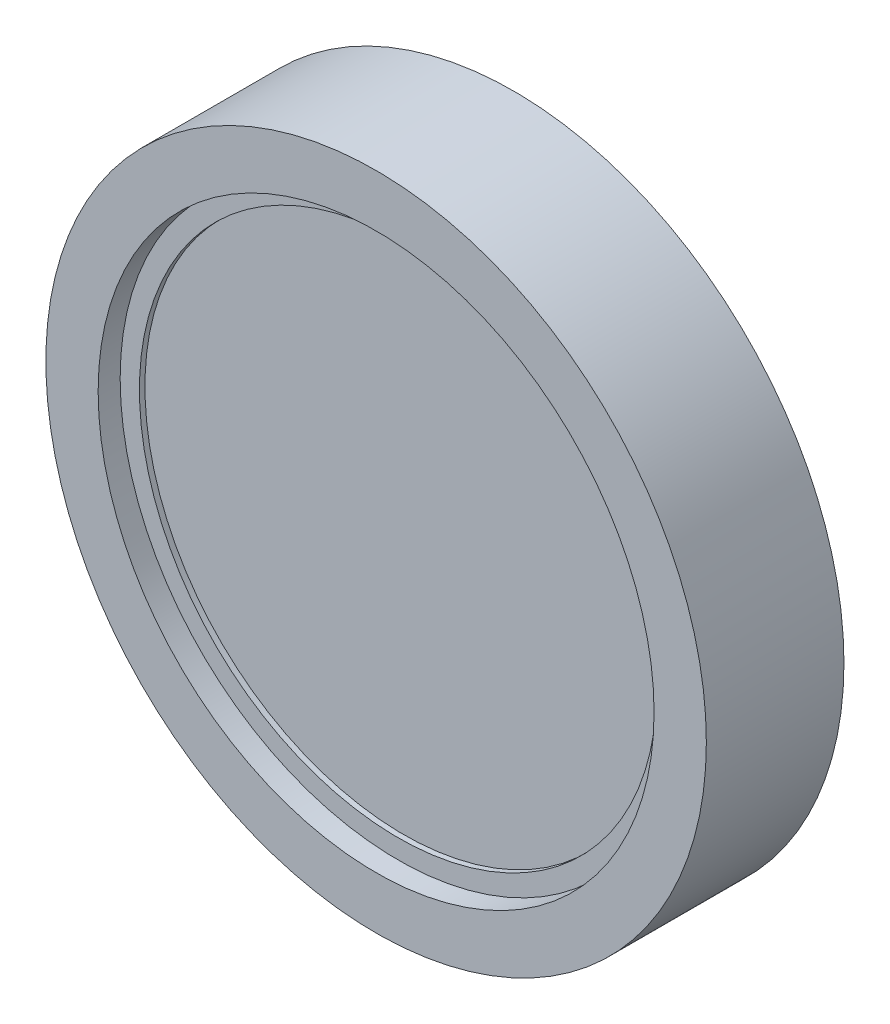
SolidWorks part; units mm, degrees
material "6061 Alloy"
ref_plane "Front Plane" through (0, 0, 0) normal (0, 0, 1) x (1, 0, 0)
ref_plane "Top Plane" through (0, 0, 0) normal (0, 1, 0) x (1, 0, 0)
ref_plane "Right Plane" through (0, 0, 0) normal (1, 0, 0) x (0, 0, -1)
sketch "Backer Main" plane through (0, 0, 0) normal (0, 0, 1) x (1, 0, 0)
  circle A0 centre (0, 0) radius 15.24
  dimension "D1" = 30.48
extrude "Boss-Extrude1" add sketch "Backer Main" against normal blind 6.35
sketch "Substrate Back Clearance" plane through (0, 0, 0) normal (0, 0, 1) x (1, 0, 0)
  circle A0 centre (0, 0) radius 11.938
  dimension "D1" = 23.876
extrude "Cut-Extrude1" cut sketch "Substrate Back Clearance" against normal blind 1.27
sketch "Substrate CSink" plane through (0, 0, 0) normal (0, 0, 1) x (1, 0, 0)
  circle A0 centre (0, 0) radius 12.827
  dimension "D1" = 25.654
extrude "Cut-Extrude2" cut sketch "Substrate CSink" against normal blind 1.016
sketch "Spring Hole" plane through (0, 0, -6.35) normal (0, 0, -1) x (-1, 0, 0)
  circle A0 centre (0, 0) radius 4.7625
  dimension "D1" = 9.525
extrude "Cut-Extrude3" cut sketch "Spring Hole" against normal blind 3.175
